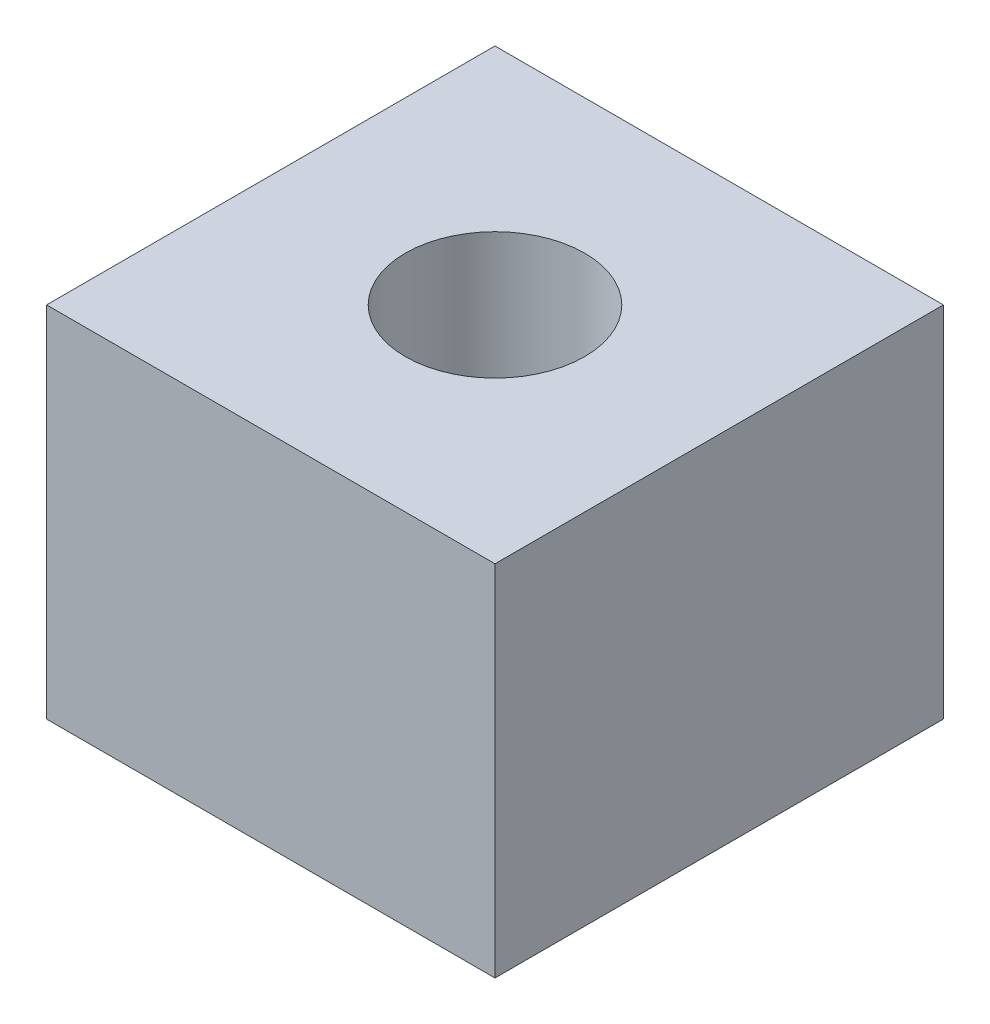
SolidWorks part; units mm, degrees
material "Brass"
ref_plane "Front Plane" through (0, 0, 0) normal (0, 0, 1) x (1, 0, 0)
ref_plane "Top Plane" through (0, 0, 0) normal (0, 1, 0) x (1, 0, 0)
ref_plane "Right Plane" through (0, 0, 0) normal (1, 0, 0) x (0, 0, -1)
sketch "Sketch1" plane through (0, 0, 0) normal (0, 1, 0) x (1, 0, 0)
  line L1 (-1.25, -1.25) -> (1.25, -1.25)
  line L2 (-1.25, -1.25) -> (-1.25, 1.25)
  line L3 (-1.25, 1.25) -> (1.25, 1.25)
  line L4 (1.25, -1.25) -> (1.25, 1.25)
  line L5 (-1.25, -1.25) -> (1.25, 1.25) construction
  line L6 (-1.25, 1.25) -> (1.25, -1.25) construction
  point P0 (0, 0)
  dimension "D1" = 2.5
  dimension "D2" = 2.5
extrude "Boss-Extrude1" add sketch "Sketch1" along normal blind 2
sketch "Sketch2" plane through (0, 2, 0) normal (0, 1, 0) x (1, 0, 0)
  circle A0 centre (0, 0) radius 0.5
  dimension "D1" = 1
extrude "Cut-Extrude1" cut sketch "Sketch2" against normal through all both and the other way through all
scale "Scale1" scale about centroid uniform scaling yes scale factor 6
